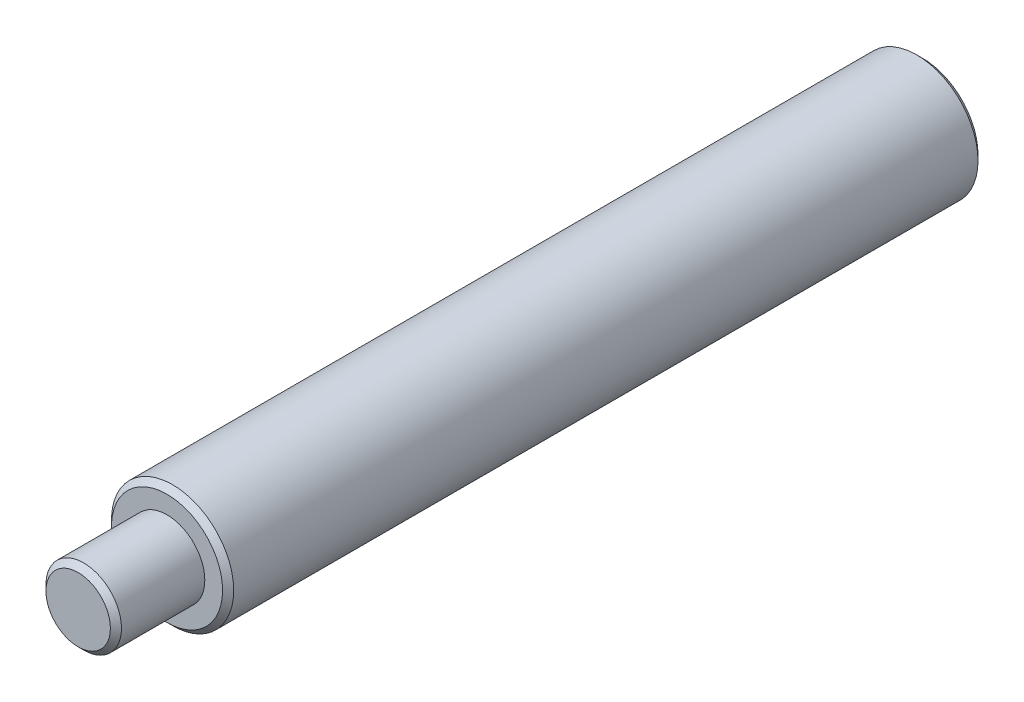
SolidWorks part; units mm, degrees
material "Q235A"
ref_plane "前视基准面" through (0, 0, 0) normal (0, 0, 1) x (1, 0, 0)
ref_plane "上视基准面" through (0, 0, 0) normal (0, 1, 0) x (1, 0, 0)
ref_plane "右视基准面" through (0, 0, 0) normal (1, 0, 0) x (0, 0, -1)
sketch "草图1" plane through (0, 0, 0) normal (0, 0, 1) x (1, 0, 0)
  circle A0 centre (0, 0) radius 5.5
  dimension "D1" = 11
extrude "拉伸1" add sketch "草图1" along normal blind 68
chamfer "倒角1" distance 0.5 angle 45 2 edges at (5.5, 0, 0) (5.5, 0, 68)
sketch "草图2" plane through (0, 0, 68) normal (0, 0, 1) x (1, 0, 0)
  circle A0 centre (0, 0) radius 3.4
  dimension "D1" = 6.8
extrude "拉伸2" add sketch "草图2" along normal blind 8
cosmetic thread "M6外螺纹" parameters "D2"=4.917
chamfer "倒角2" distance 0.5 angle 45 1 edges at (3.4, 0, 76)
hole_wizard "M5 螺纹孔1" positions "草图4" profile "草图3" tap size "M5" standard "GB"
sketch "草图4" plane through (0, 0, 0) normal (0, 0, -1) x (-1, 0, 0)
  point P1 (0, 0)
sketch "草图3" plane through (0, 0, 0) normal (1, 0, 0) x (0, 1, 0)
  line L0 (0, 0) -> (0, 13.6618)
  line L1 (0, 13.6618) -> (2.1, 12.4)
  line L2 (2.1, 12.4) -> (2.1, 0)
  line L5 (2.1, 0) -> (0, 0)
  line L10 (0, 13.6618) -> (-2.1, 12.4) construction
  line L11 (0, -6.35) -> (0, 107.95) construction
  dimension "螺纹孔钻头直径" = 4.2
  dimension "螺纹孔钻头深度" = 12.4
  dimension "导头角度" = 118
cosmetic thread "M5内螺纹" parameters "D1"=10, "D2"=5
chamfer "倒角3" distance 0.5 angle 45 1 edges at (-2.1, 0, 0)
sketch "草图5" plane through (0, 0, 0) normal (0, 0, 1) x (1, 0, 0)
  line L0 (0, 0) -> (0, 5) construction
  line L1 (-5, 8) -> (5, 8)
  line L2 (-5, 8) -> (-5, 5)
  line L3 (-5, 5) -> (5, 5)
  line L4 (5, 8) -> (5, 5)
  dimension "D1" = 5
  dimension "D2" = 3
  dimension "D3" = 10
extrude "拉伸3" [suppressed] cut sketch "草图5" along normal blind 13
mirror "镜向1" [suppressed] about plane through (0, 0, 0) normal (0, 1, 0)
